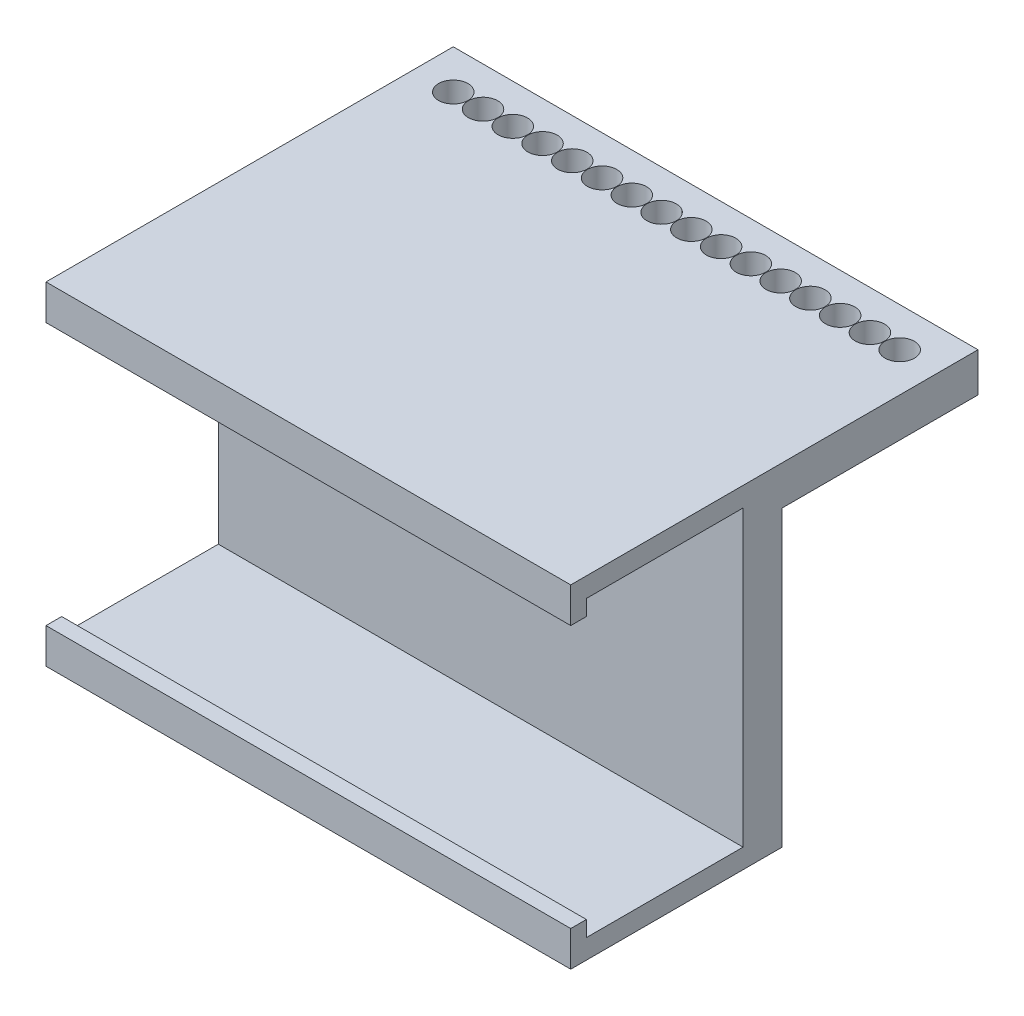
SolidWorks part; units mm, degrees
ref_plane "Front Plane" through (0, 0, 0) normal (0, 0, 1) x (1, 0, 0)
ref_plane "Top Plane" through (0, 0, 0) normal (0, 1, 0) x (1, 0, 0)
ref_plane "Right Plane" through (0, 0, 0) normal (1, 0, 0) x (0, 0, -1)
sketch "Sketch1" plane through (0, 0, 0) normal (0, 1, 0) x (1, 0, 0)
  line L0 (-82.0316, 4.0821) -> (-88.3816, 4.0821) construction
  line L1 (-88.3816, 10.4321) -> (-3.2916, 10.4321)
  line L2 (-88.3816, 10.4321) -> (-88.3816, -27.6679)
  line L3 (-88.3816, -27.6679) -> (-3.2916, -27.6679)
  line L4 (-3.2916, 10.4321) -> (-3.2916, -27.6679)
  circle A0 centre (-82.0316, 4.0821) radius 2.3813
  circle A16 centre (-77.2056, 4.0821) radius 2.3813
  circle A17 centre (-72.3796, 4.0821) radius 2.3813
  circle A18 centre (-67.5536, 4.0821) radius 2.3813
  circle A19 centre (-62.7276, 4.0821) radius 2.3813
  circle A20 centre (-57.9016, 4.0821) radius 2.3813
  circle A21 centre (-53.0756, 4.0821) radius 2.3813
  circle A22 centre (-48.2496, 4.0821) radius 2.3813
  circle A23 centre (-43.4236, 4.0821) radius 2.3813
  circle A24 centre (-38.5976, 4.0821) radius 2.3813
  circle A25 centre (-33.7716, 4.0821) radius 2.3813
  circle A26 centre (-28.9456, 4.0821) radius 2.3813
  circle A27 centre (-24.1196, 4.0821) radius 2.3813
  circle A28 centre (-19.2936, 4.0821) radius 2.3813
  circle A29 centre (-14.4676, 4.0821) radius 2.3813
  circle A30 centre (-9.6416, 4.0821) radius 2.3813
  dimension "D4" = 4.7625
  dimension "D1" = 6.35
  dimension "D2" = 31.75
  dimension "D3" = 6.35
  dimension "D6" = 6.35
  dimension "D5" = 16
extrude "Boss-Extrude1" add sketch "Sketch1" along normal blind 6.35
sketch "Sketch2" plane through (0, 0, 0) normal (0, -1, 0) x (1, 0, 0)
  line L0 (-3.2916, 27.6679) -> (-3.2916, -10.4321) construction
  line L1 (-88.3816, 27.6679) -> (-3.2916, 27.6679)
  line L2 (-88.3816, 27.6679) -> (-88.3816, 21.3179)
  line L3 (-88.3816, 21.3179) -> (-3.2916, 21.3179)
  line L4 (-3.2916, 27.6679) -> (-3.2916, 21.3179)
  dimension "D1" = 6.35
extrude "Boss-Extrude2" add sketch "Sketch2" along normal blind 47.625
sketch "Sketch3" plane through (0, 0, 27.6679) normal (0, 0, 1) x (1, 0, 0)
  line L0 (-3.2916, 6.35) -> (-3.2916, -47.625) construction
  line L1 (-88.3816, 6.35) -> (-3.2916, 6.35)
  line L2 (-88.3816, 6.35) -> (-88.3816, 3.175)
  line L3 (-88.3816, 3.175) -> (-3.2916, 3.175)
  line L4 (-3.2916, 6.35) -> (-3.2916, 3.175)
  line L6 (-88.3816, -47.625) -> (-3.2916, -47.625)
  line L7 (-88.3816, -47.625) -> (-88.3816, -44.45)
  line L8 (-88.3816, -44.45) -> (-3.2916, -44.45)
  line L9 (-3.2916, -47.625) -> (-3.2916, -44.45)
  dimension "D1" = 3.175
extrude "Boss-Extrude3" add sketch "Sketch3" along normal blind 27.94
sketch "Sketch4" plane through (-3.2916, 0, 0) normal (1, 0, 0) x (0, 0, -1)
  line L1 (-55.6079, 3.175) -> (-53.0679, 3.175)
  line L2 (-55.6079, 3.175) -> (-55.6079, 0.635)
  line L3 (-55.6079, 0.635) -> (-53.0679, 0.635)
  line L4 (-53.0679, 3.175) -> (-53.0679, 0.635)
  line L5 (-55.6079, -44.45) -> (-53.0679, -44.45)
  line L6 (-55.6079, -44.45) -> (-55.6079, -41.91)
  line L7 (-55.6079, -41.91) -> (-53.0679, -41.91)
  line L8 (-53.0679, -44.45) -> (-53.0679, -41.91)
  dimension "D1" = 2.54
extrude "Boss-Extrude4" add sketch "Sketch4" against normal up to surface (85.09 mm away) up to face at (-88.3816, -16.51, 29.9539)
